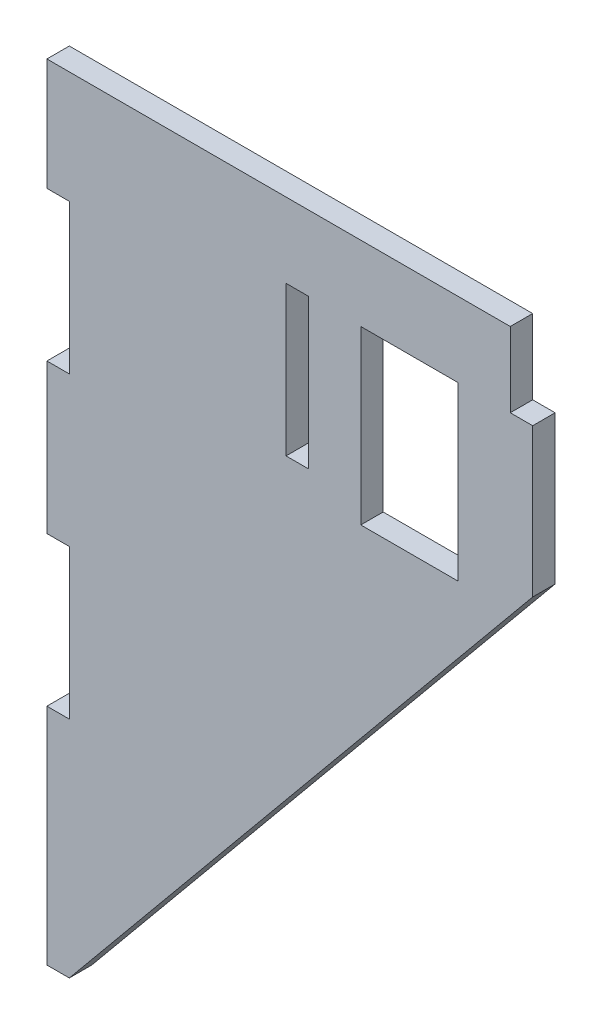
SolidWorks part; units mm, degrees
material "Acrilico TEC"
ref_plane "Front Plane" through (0, 0, 0) normal (0, 0, 1) x (1, 0, 0)
ref_plane "Top Plane" through (0, 0, 0) normal (0, 1, 0) x (1, 0, 0)
ref_plane "Right Plane" through (0, 0, 0) normal (1, 0, 0) x (0, 0, -1)
sketch "Sketch1" plane through (0, 0, 0) normal (0, 0, 1) x (1, 0, 0)
  line L0 (-3, 70) -> (-3, 50)
  line L1 (-3, 50) -> (0, 50)
  line L2 (0, 50) -> (0, 30)
  line L3 (0, 30) -> (-3, 30)
  line L4 (-3, 30) -> (-3, 0)
  line L5 (-3, 70) -> (0, 70)
  line L6 (0, 70) -> (0, 90)
  line L7 (0, 90) -> (-3, 90)
  line L8 (-3, 90) -> (-3, 105)
  line L9 (-3, 105) -> (15, 105)
  line L10 (15, 105) -> (15, 90) construction
  line L11 (-3, 0) -> (0, 0)
  line L12 (15, 105) -> (59, 105)
  line L13 (39, 72) -> (52, 72)
  line L14 (29, 95) -> (32, 95)
  line L15 (29, 75) -> (29, 95)
  line L16 (32, 75) -> (29, 75)
  line L17 (59, 105) -> (59, 95)
  line L18 (59, 95) -> (62, 95)
  line L19 (62, 95) -> (62, 75.1515)
  line L20 (52, 95) -> (52, 72)
  line L21 (39, 72) -> (39, 95)
  line L22 (0, 0) -> (62, 75.1515)
  line L23 (0, 0) -> (26.7162, 0) construction
  line L24 (39, 95) -> (52, 95)
  line L25 (32, 75) -> (32, 95)
  dimension "D1" = 15
  dimension "D2" = 20
  dimension "D3" = 20
  dimension "D4" = 20
  dimension "D5" = 30
  dimension "D6" = 3
  dimension "D7" = 3
  dimension "D8" = 15
  dimension "D9" = 15
  dimension "D10" = 44
  dimension "D11" = 3
  dimension "D12" = 10
  dimension "D13" = 7
  dimension "D14" = 20
  dimension "D15" = 3
  dimension "D16" = 3
  dimension "D17" = 14
  dimension "D18" = 10
  dimension "D19" = 50.477
  dimension "D20" = 23
  dimension "D21" = 19.8485
extrude "Boss-Extrude1" add sketch "Sketch1" along normal blind 3
